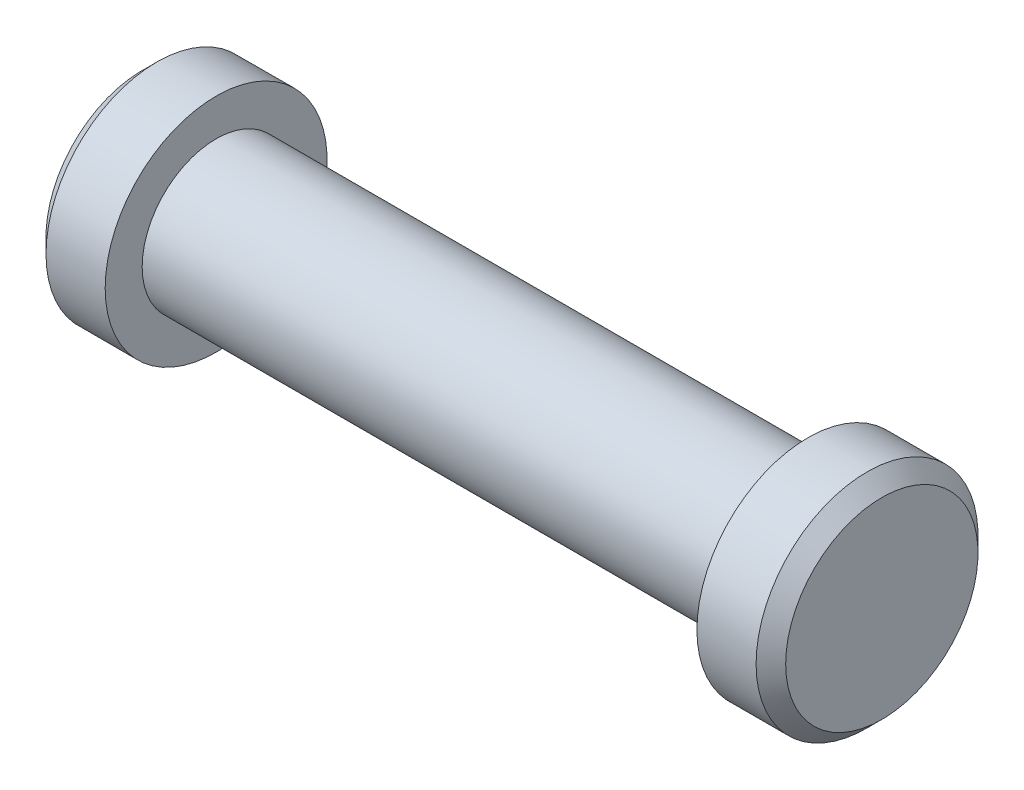
SolidWorks part; units mm, degrees
ref_plane "Front Plane" through (0, 0, 0) normal (0, 0, 1) x (1, 0, 0)
ref_plane "Top Plane" through (0, 0, 0) normal (0, 1, 0) x (1, 0, 0)
ref_plane "Right Plane" through (0, 0, 0) normal (1, 0, 0) x (0, 0, -1)
other "Configuration Table"
sketch "Sketch1" plane through (0, 0, 0) normal (0, 0, 1) x (1, 0, 0)
  line L0 (-6.35, 0) -> (6.35, 0) construction
  line L1 (-6.35, 0) -> (-6.35, 1.905)
  line L2 (-6.35, 1.905) -> (-5.08, 1.905)
  line L3 (-5.08, 1.905) -> (-5.08, 1.27)
  line L4 (-5.08, 1.27) -> (5.08, 1.27)
  line L5 (5.08, 1.27) -> (5.08, 1.905)
  line L6 (5.08, 1.905) -> (6.35, 1.905)
  line L7 (6.35, 1.905) -> (6.35, 0)
  line L8 (-6.35, 0) -> (6.35, 0)
  dimension "D1" = 10.16
  dimension "D2" = 2.54
  dimension "D3" = 3.81
  dimension "D4" = 1.27
revolve "Revolve1" add sketch "Sketch1" angle 360 about L0
chamfer "Chamfer1" distance 0.254 angle 45 2 edges at (-6.35, 0, 1.905) (6.35, 0, 1.905)
scale "Scale1" scale about centroid uniform scaling yes scale factor 1.5
